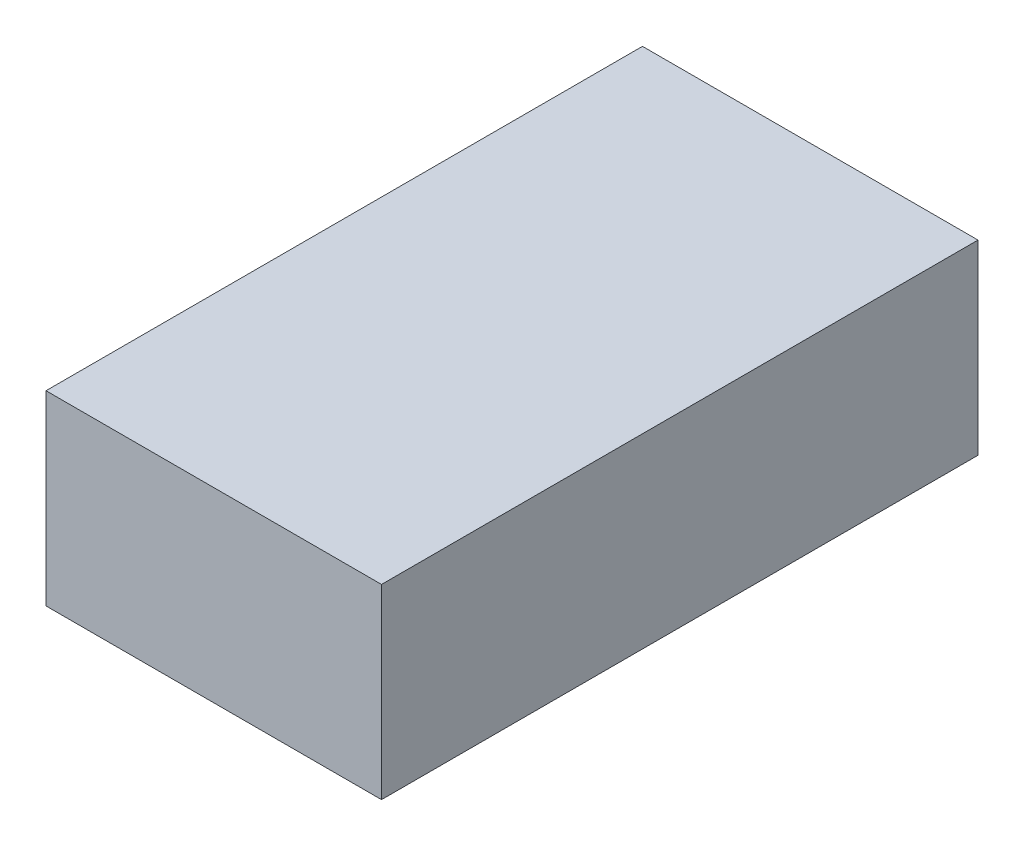
SolidWorks part; units mm, degrees
material "Alloy Steel (SS)"
ref_plane "Front Plane" through (0, 0, 0) normal (0, 0, 1) x (1, 0, 0)
ref_plane "Top Plane" through (0, 0, 0) normal (0, 1, 0) x (1, 0, 0)
ref_plane "Right Plane" through (0, 0, 0) normal (1, 0, 0) x (0, 0, -1)
sketch "Sketch1" plane through (0, 0, 0) normal (0, 0, 1) x (1, 0, 0)
  line L1 (-28.575, -15.875) -> (28.575, -15.875)
  line L2 (-28.575, -15.875) -> (-28.575, 15.875)
  line L3 (-28.575, 15.875) -> (28.575, 15.875)
  line L4 (28.575, -15.875) -> (28.575, 15.875)
  line L5 (-28.575, -15.875) -> (28.575, 15.875) construction
  line L6 (-28.575, 15.875) -> (28.575, -15.875) construction
  point P0 (0, 0)
  dimension "D1" = 31.75
  dimension "D2" = 57.15
extrude "Boss-Extrude1" add sketch "Sketch1" along normal blind 101.6
